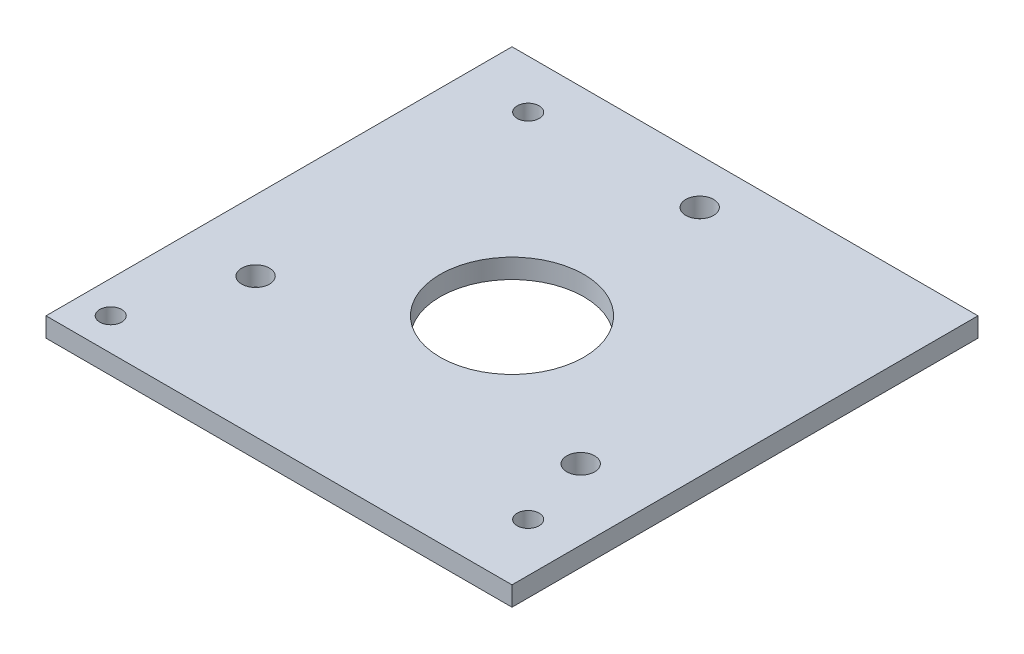
SolidWorks part; units mm, degrees
ref_plane "前视基准面" through (0, 0, 0) normal (0, 0, 1) x (1, 0, 0)
ref_plane "上视基准面" through (0, 0, 0) normal (0, 1, 0) x (1, 0, 0)
ref_plane "右视基准面" through (0, 0, 0) normal (1, 0, 0) x (0, 0, -1)
sketch "草图3" plane through (0, 0, 0) normal (0, 1, 0) x (1, 0, 0)
  line L1 (36, -36) -> (-36, -36)
  line L2 (36, -36) -> (36, 36)
  line L3 (36, 36) -> (-36, 36)
  line L4 (-36, -36) -> (-36, 36)
  line L5 (36, -36) -> (-36, 36) construction
  line L6 (36, 36) -> (-36, -36) construction
  circle A0 centre (0, 0) radius 11.1
  circle A1 centre (0, 0) radius 29 construction
  circle A2 centre (0, 29) radius 2.15
  circle A3 centre (25.1147, -14.5) radius 2.15
  circle A4 centre (-25.1147, -14.5) radius 2.15
  circle A5 centre (0, 0) radius 33.5 construction
  circle A6 centre (-26, 28.5) radius 1.7
  circle A7 centre (-31, -31) radius 1.7
  circle A8 centre (28.5, -26) radius 1.7
  point P12 (0, 0)
  dimension "D1" = 22.2
  dimension "D2" = 58
  dimension "D3" = 4.3
  dimension "D5" = 67
  dimension "D7" = 3.4
  dimension "D8" = 10
  dimension "D9" = 7.5
  dimension "D10" = 3.4
  dimension "D11" = 5
  dimension "D12" = 3.4
  dimension "D13" = 7.5
  dimension "D14" = 10
  dimension "D6" = 72
  dimension "D4" = 3
extrude "凸台-拉伸1" add sketch "草图3" along normal blind 3
